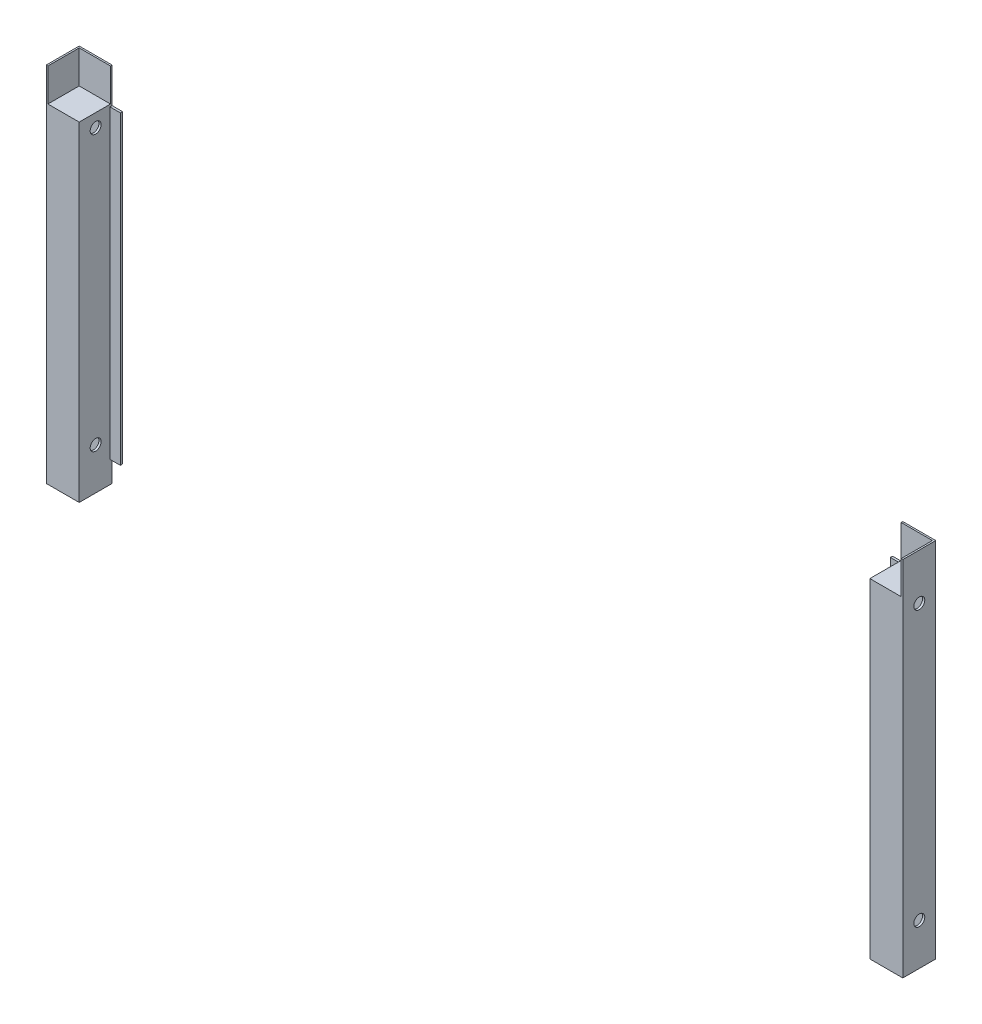
SolidWorks part; units mm, degrees
other "Markup1"
sketch "Sketch8" plane through (-15, 330, 15) normal (-0.6194, 0.0982, 0.7789) x (0.7832, 0.0097, 0.6217)
ref_plane "Front Plane" through (0, 0, 0) normal (0, 0, 1) x (1, 0, 0)
ref_plane "Top Plane" through (0, 0, 0) normal (0, 1, 0) x (1, 0, 0)
ref_plane "Right Plane" through (0, 0, 0) normal (1, 0, 0) x (0, 0, -1)
sketch "Sketch1" plane through (0, 0, 0) normal (0, 1, 0) x (1, 0, 0)
  line L1 (-15, 15) -> (15, 15)
  line L2 (-15, 15) -> (-15, -15)
  line L3 (-15, -15) -> (15, -15)
  line L4 (15, 15) -> (15, -15)
  line L5 (-15, 15) -> (15, -15) construction
  line L6 (-15, -15) -> (15, 15) construction
  point P0 (0, 0)
  dimension "D1" = 30
  dimension "D2" = 30
extrude "Boss-Extrude1" add sketch "Sketch1" along normal blind 300
shell "Shell1" thickness 2
sketch "Sketch3" plane through (-15, 0, 0) normal (-1, 0, 0) x (0, 0, 1)
  line L0 (-15, 300) -> (-15, 330)
  line L1 (-15, 300) -> (15, 300)
  line L2 (15, 300) -> (15, 330)
  line L3 (15, 330) -> (-15, 330)
  dimension "D1" = 30
extrude "Boss-Extrude2" add sketch "Sketch3" against normal blind 1.5 separate body
sketch "Sketch4" plane through (0, 0, -15) normal (0, 0, -1) x (-1, 0, 0)
  line L0 (15, 300) -> (-15, 300)
  line L1 (-15, 300) -> (-15, 330)
  line L2 (-15, 330) -> (15, 330)
  line L3 (15, 330) -> (15, 300) construction
  line L4 (15, 330) -> (15, 300)
  dimension "D1" = 30
extrude "Boss-Extrude3" add sketch "Sketch4" against normal blind 1.5
sketch "Sketch5" plane through (-15, 0, 0) normal (-1, 0, 0) x (0, 0, 1)
  line L0 (0, 330) -> (0, 288) construction
  line L2 (0, 293) -> (0, 288) construction
  line L3 (15, 330) -> (-15, 330) construction
  line L4 (0, 0) -> (0, 38) construction
  circle A0 centre (0, 288) radius 5
  circle A1 centre (0, 38) radius 5
  dimension "D2" = 10
  dimension "D4" = 10
  dimension "D1" = 42
  dimension "D3" = 38
extrude "Cut-Extrude1" cut sketch "Sketch5" against normal through all
ref_plane "Plane1" through (375, 0, 0) normal (-1, 0, 0) x (0, 0, 1)
ref_plane "Plane2" through (0, 20, 0) normal (0, -1, 0) x (-1, 0, 0)
sketch "Sketch7" plane through (0, 20, 0) normal (0, -1, 0) x (-1, 0, 0)
  line L6 (-13, 0) -> (13, 0) construction
  line L7 (-13, -13) -> (-13, 13) construction
  line L8 (13, 13) -> (13, -13) construction
  line L9 (-13, 13) -> (-13, 15)
  line L10 (-13, 15) -> (-15, 15)
  line L11 (-13, 13) -> (-24.4, 13)
  line L12 (-15, 15) -> (-24.4, 15)
  line L13 (-24.4, 13) -> (-24.4, 15)
  dimension "D1" = 9.4
extrude "Boss-Extrude4" add sketch "Sketch7" against normal blind 278
mirror "Mirror5" about plane through (375, 0, 0) normal (-1, 0, 0) of bodies 106
